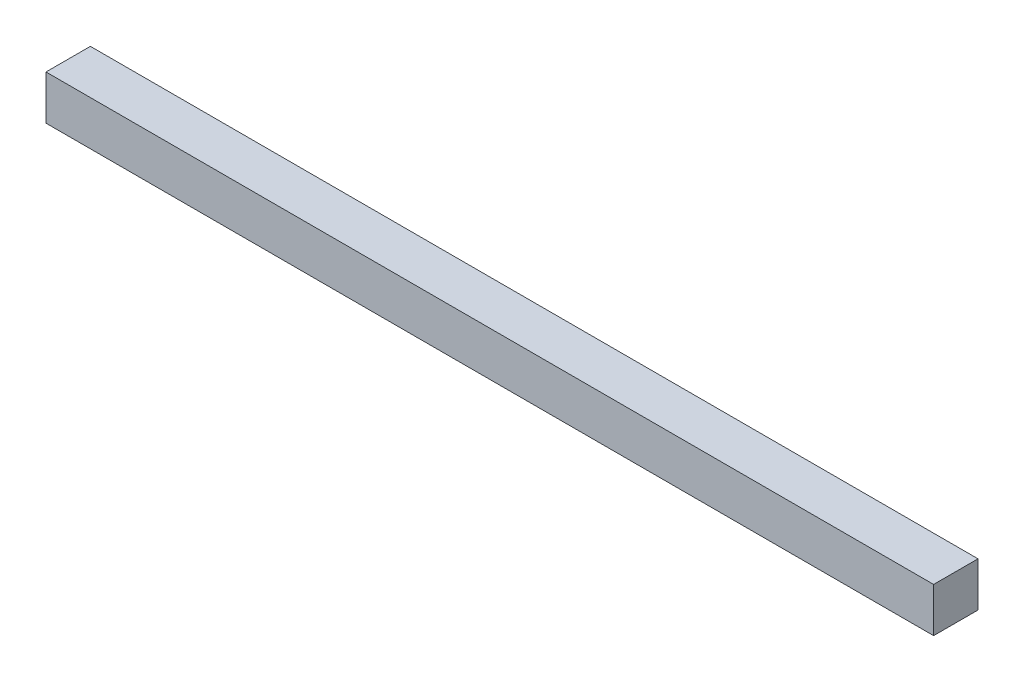
SolidWorks part; units mm, degrees
ref_plane "Front Plane" through (0, 0, 0) normal (0, 0, 1) x (1, 0, 0)
ref_plane "Top Plane" through (0, 0, 0) normal (0, 1, 0) x (1, 0, 0)
ref_plane "Right Plane" through (0, 0, 0) normal (1, 0, 0) x (0, 0, -1)
sketch "Sketch1" plane through (0, 0, 0) normal (1, 0, 0) x (0, 0, -1)
  line L1 (-12.7, 12.7) -> (12.7, 12.7)
  line L2 (-12.7, 12.7) -> (-12.7, -12.7)
  line L3 (-12.7, -12.7) -> (12.7, -12.7)
  line L4 (12.7, 12.7) -> (12.7, -12.7)
  line L5 (-12.7, 12.7) -> (12.7, -12.7) construction
  line L6 (-12.7, -12.7) -> (12.7, 12.7) construction
  point P0 (0, 0)
  dimension "D1" = 25.4
extrude "Boss-Extrude1" add sketch "Sketch1" along normal blind 508
